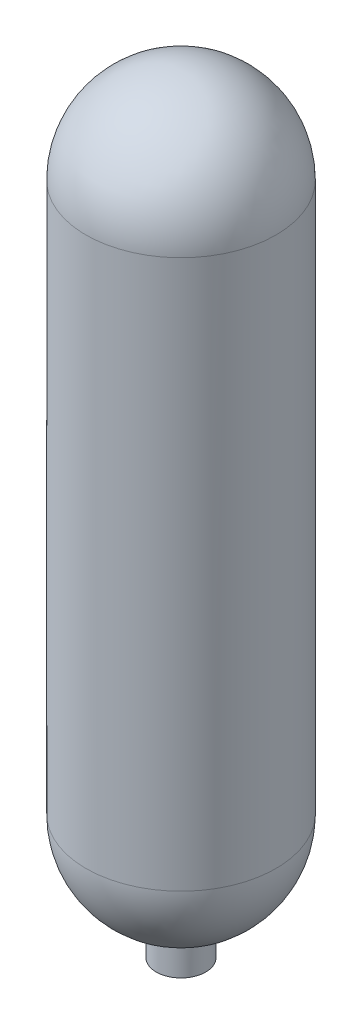
SolidWorks part; units mm, degrees
ref_plane "Front Plane" through (0, 0, 0) normal (0, 0, 1) x (1, 0, 0)
ref_plane "Top Plane" through (0, 0, 0) normal (0, 1, 0) x (1, 0, 0)
ref_plane "Right Plane" through (0, 0, 0) normal (1, 0, 0) x (0, 0, -1)
sketch "Sketch1" plane through (0, 0, 0) normal (0, 0, 1) x (1, 0, 0)
  line L0 (0, 0) -> (0, 747.3154) construction
  line L1 (0, 0) -> (15, 0)
  line L2 (15, 0) -> (15, 20)
  line L3 (57.5, 407.5) -> (57.5, 75.509)
  line L4 (0, 465) -> (0, 0)
  arc A0 (57.5, 407.5) -> (0, 465) centre (0, 407.5) ccw
  arc A2 (15, 20) -> (57.5, 75.509) centre (0, 75.509) ccw
  dimension "D1" = 115
  dimension "D2" = 30
  dimension "D3" = 20
  dimension "D4" = 465
revolve "Revolve1" add sketch "Sketch1" angle 360 about L0
hole_wizard "M18x1.5 Tapped Hole1" positions "Sketch2" profile "Sketch3" tap size "M18x1.5" standard "ANSI Metric"
sketch "Sketch2" plane through (0, 0, 0) normal (0, -1, 0) x (-1, 0, 0)
  point P0 (0, 0)
sketch "Sketch3" plane through (0, 0, 0) normal (1, 0, 0) x (0, 0, -1)
  line L0 (0, 0) -> (0, 20)
  line L1 (0, 20) -> (8.25, 15.0429)
  line L2 (8.25, 15.0429) -> (8.25, 0)
  line L5 (8.25, 0) -> (0, 0)
  line L10 (0, 20) -> (-8.25, 15.0429) construction
  line L11 (0, -6.35) -> (0, 107.95) construction
  dimension "Tap Drill Dia." = 16.5
  dimension "Tap Drill Depth" = 20
  dimension "Drill Angle" = 118
cosmetic thread "Hole Thread1" parameters "D1"=36, "D2"=18
fillet "Fillet1" radius 5 1 edges at (0, 20, -15)
sketch "Sketch4" plane through (0, 0, 0) normal (0, 0, 1) x (1, 0, 0)
  line L0 (0, 0) -> (0, 652.9616) construction
  line L3 (8.25, 15.0429) -> (8.25, 25.7696)
  line L4 (52.5, 75.509) -> (52.5, 407.5)
  line L5 (52.5, 75.509) -> (52.5, 407.5)
  line L6 (8.25, 25.7696) -> (16.8, 25.7696)
  line L7 (8.25, 15.0429) -> (0, 15.0429)
  line L8 (8.25, 15.0429) -> (-8.25, 15.0429) construction
  line L9 (0, 15.0429) -> (0, 460)
  arc A6 (52.5, 407.5) -> (-52.5, 407.5) centre (0, 407.5) ccw
  arc A7 (16.8, 25.7696) -> (52.5, 75.509) centre (0, 75.509) ccw
  arc A8 (52.5, 407.5) -> (0, 460) centre (0, 407.5) ccw
  arc A9 (16.8, 25.7696) -> (52.5, 75.509) centre (0, 75.509) ccw
  dimension "D1" = 5
revolve "Cut-Revolve1" cut sketch "Sketch4" angle 360 about L0
